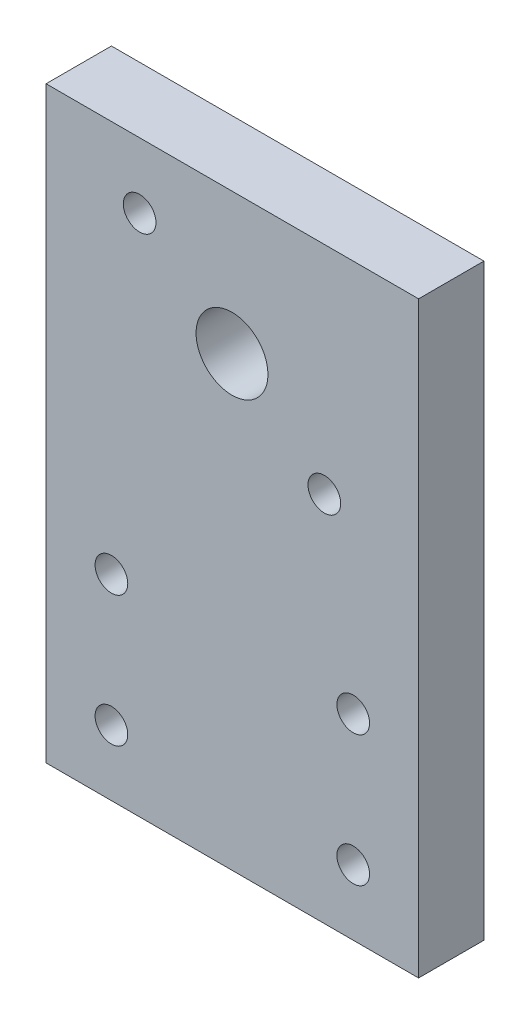
SolidWorks part; units mm, degrees
ref_plane "Front Plane" through (0, 0, 0) normal (0, 0, 1) x (1, 0, 0)
ref_plane "Top Plane" through (0, 0, 0) normal (0, 1, 0) x (1, 0, 0)
ref_plane "Right Plane" through (0, 0, 0) normal (1, 0, 0) x (0, 0, -1)
sketch "Sketch1" plane through (0, 0, 0) normal (0, 0, 1) x (1, 0, 0)
  line L0 (0, 0) -> (57, 0)
  line L1 (57, 0) -> (57, 90)
  line L2 (57, 90) -> (0, 90)
  line L3 (0, 90) -> (0, 0)
  dimension "D1" = 57
  dimension "D2" = 90
extrude "Boss-Extrude1" add sketch "Sketch1" along normal blind 10
sketch "Sketch2" plane through (0, 0, 10) normal (0, 0, 1) x (1, 0, 0)
  line L0 (57, 0) -> (57, 90) construction
  line L1 (0, 0) -> (57, 0) construction
  line L2 (57, 90) -> (0, 90) construction
  line L4 (33.989, 63.9224) -> (28.45, 68.45) construction
  line L5 (28.45, 68.45) -> (22.8564, 73.0222) construction
  circle A0 centre (47, 10) radius 2.5
  circle A1 centre (10, 30) radius 2.5
  circle A2 centre (47, 30) radius 2.5
  circle A3 centre (10, 10) radius 2.5
  circle A4 centre (28.45, 68.45) radius 5.5
  circle A5 centre (42.5801, 56.9) radius 2.5
  circle A6 centre (14.3199, 80) radius 2.5
  point P22 (14.2422, 79.9043)
  dimension "D1" = 5
  dimension "D6" = 11
  dimension "D9" = 5
  dimension "D2" = 10
  dimension "D3" = 37
  dimension "D4" = 10
  dimension "D5" = 20
  dimension "D7" = 21.55
  dimension "D8" = 28.55
  dimension "D10" = 18.25
  dimension "D11" = 18.25
  dimension "D12" = 10
extrude "Cut-Extrude1" cut sketch "Sketch2" against normal blind 10
